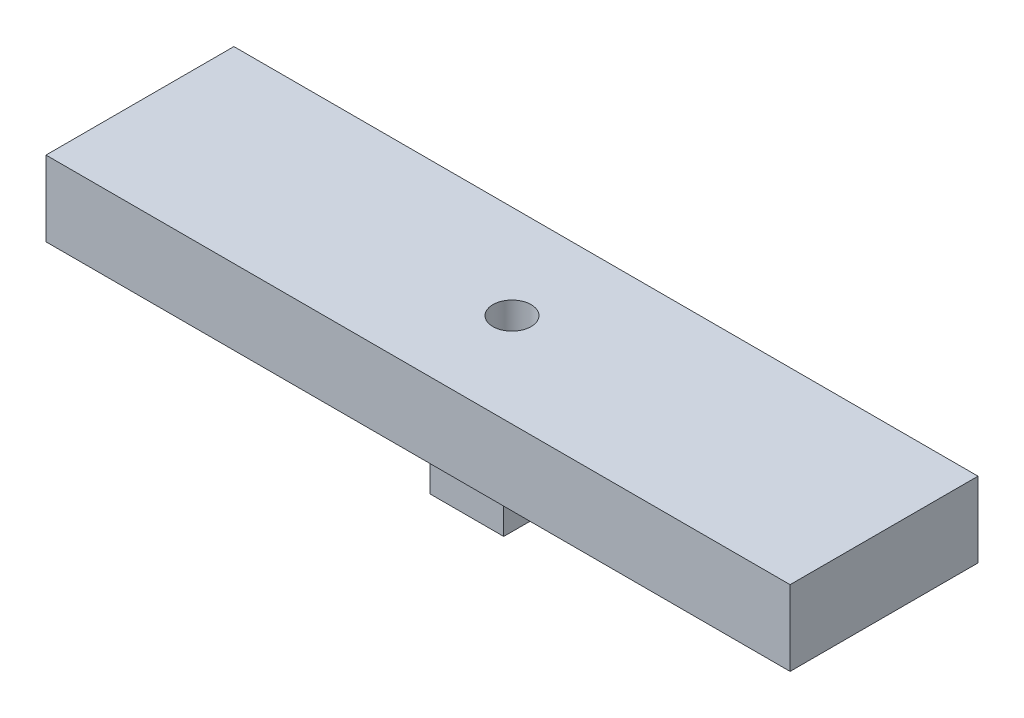
SolidWorks part; units mm, degrees
ref_plane "Front Plane" through (0, 0, 0) normal (0, 0, 1) x (1, 0, 0)
ref_plane "Top Plane" through (0, 0, 0) normal (0, 1, 0) x (1, 0, 0)
ref_plane "Right Plane" through (0, 0, 0) normal (1, 0, 0) x (0, 0, -1)
sketch "Sketch1" plane through (0, 0, 0) normal (0, 1, 0) x (1, 0, 0)
  line L0 (-49.5, -12.5) -> (-49.5, 12.5)
  line L7 (-49.5, 12.5) -> (49.5, 12.5)
  line L8 (49.5, -12.5) -> (49.5, 12.5)
  line L9 (-49.5, -12.5) -> (49.5, -12.5)
  point P0 (0, 0)
extrude "Boss-Extrude1" add sketch "Sketch1" along normal blind 10
sketch "Sketch9" plane through (0, 0, 0) normal (0, -1, 0) x (1, 0, 0)
  line L1 (-4.9, 6) -> (4.9, 6)
  line L2 (-4.9, 6) -> (-4.9, -6)
  line L3 (-4.9, -6) -> (4.9, -6)
  line L4 (4.9, 6) -> (4.9, -6)
  line L5 (-4.9, 6) -> (4.9, -6) construction
  line L6 (-4.9, -6) -> (4.9, 6) construction
  point P0 (0, 0)
  dimension "D1" = 9.8
  dimension "D2" = 12
extrude "Boss-Extrude9" add sketch "Sketch9" along normal blind 10
sketch "Sketch10" plane through (0, 10, 0) normal (0, 1, 0) x (1, 0, 0)
  line L0 (0, 12.5) -> (0, -12.5) construction
  line L1 (49.5, 12.5) -> (-49.5, 12.5) construction
  line L2 (-49.5, -12.5) -> (49.5, -12.5) construction
  circle A0 centre (0, 0) radius 2.54
  dimension "D1" = 5.08
extrude "Cut-Extrude1" cut sketch "Sketch10" against normal blind 5.22
sketch "Sketch11" plane through (4.9, 0, 0) normal (1, 0, 0) x (0, 0, -1)
  line L0 (0, -10) -> (0, -6) construction
  line L1 (6, -10) -> (-6, -10) construction
  circle A0 centre (0, -6) radius 2.05
  dimension "D2" = 4.1
  dimension "D1" = 4
extrude "Cut-Extrude2" cut sketch "Sketch11" against normal blind 10
